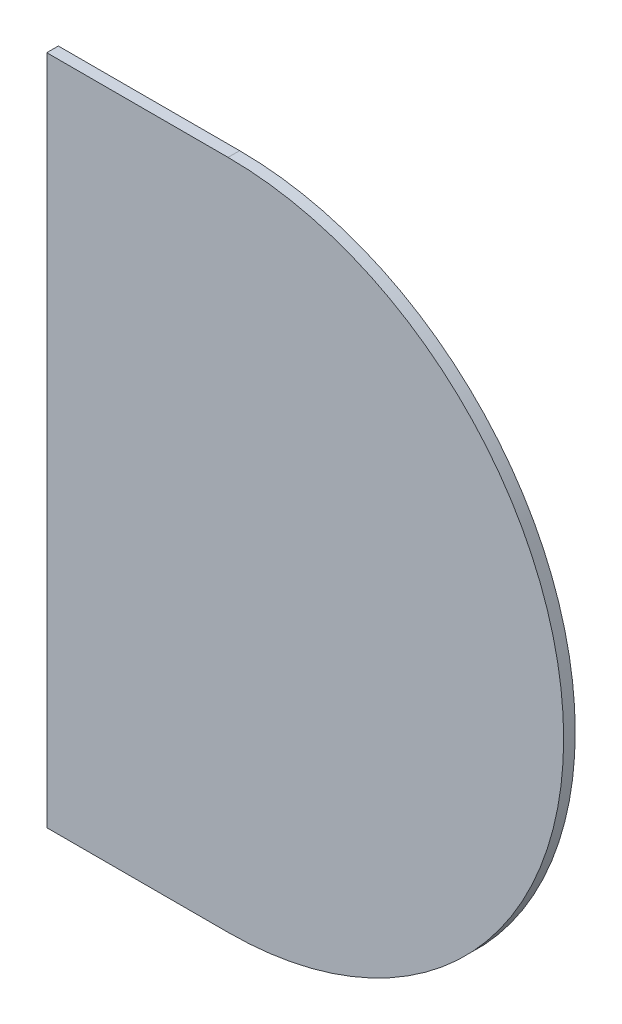
SolidWorks part; units mm, degrees
ref_plane "Front Plane" through (0, 0, 0) normal (0, 0, 1) x (1, 0, 0)
ref_plane "Top Plane" through (0, 0, 0) normal (0, 1, 0) x (1, 0, 0)
ref_plane "Right Plane" through (0, 0, 0) normal (1, 0, 0) x (0, 0, -1)
sketch "Sketch1" plane through (0, 0, 0) normal (0, 0, 1) x (1, 0, 0)
  line L1 (0, 0) -> (470, 0)
  line L2 (0, 0) -> (0, 1740)
  line L3 (0, 1740) -> (470, 1740)
  line L4 (470, 0) -> (470, 1740) construction
  arc A0 (470, 1740) -> (470, 0) centre (470, 870) cw
  dimension "D1" = 470
  dimension "D2" = 1740
extrude "Boss-Extrude1" add sketch "Sketch1" along normal blind 30
